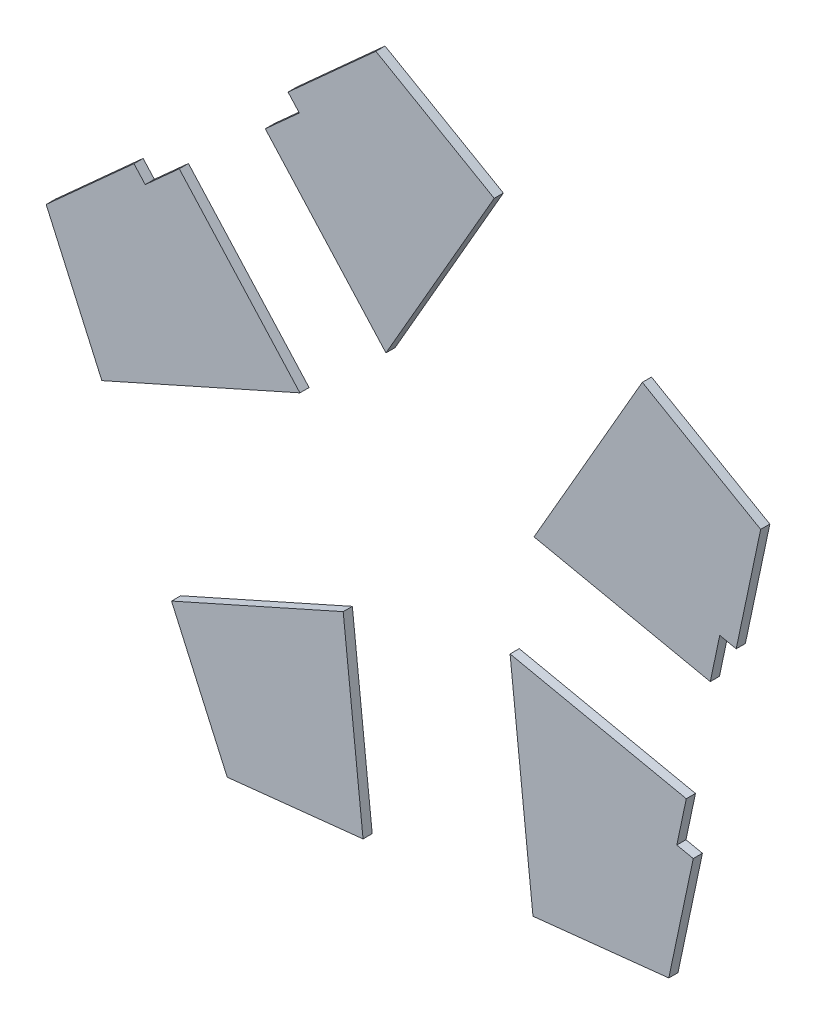
SolidWorks part; units mm, degrees
ref_plane "Front Plane" through (0, 0, 0) normal (0, 0, 1) x (1, 0, 0)
ref_plane "Top Plane" through (0, 0, 0) normal (0, 1, 0) x (1, 0, 0)
ref_plane "Right Plane" through (0, 0, 0) normal (1, 0, 0) x (0, 0, -1)
sketch "Sketch15" plane through (0, 0, 0) normal (0, 0, 1) x (1, 0, 0)
  line L0 (37.7834, -91.019) -> (30.8688, -25.9063)
  line L2 (30.8688, -25.9063) -> (88.5339, -38.0985)
  line L3 (88.5339, -38.0985) -> (85.4311, -52.774)
  line L4 (85.4311, -52.774) -> (90.8121, -53.9117)
  line L5 (90.8121, -53.9117) -> (82.808, -91.7686)
  line L6 (82.808, -91.7686) -> (38.3642, -96.4882)
  line L7 (38.3642, -96.4882) -> (37.7834, -91.019)
  line L8 (74.1362, 72.7022) -> (38.7131, 11.1945)
  line L10 (38.7131, 11.1945) -> (96.3782, -0.9976)
  line L11 (96.3782, -0.9976) -> (99.4811, 13.6779)
  line L12 (99.4811, 13.6779) -> (104.8621, 12.5402)
  line L13 (104.8621, 12.5402) -> (112.8662, 50.3971)
  line L14 (112.8662, 50.3971) -> (74.1362, 72.7022)
  line L15 (25.6771, 100.6105) -> (-9.7461, 39.1028)
  line L17 (-9.7461, 39.1028) -> (-49.2317, 82.8612)
  line L18 (-49.2317, 82.8612) -> (-38.0954, 92.9102)
  line L19 (-38.0954, 92.9102) -> (-41.78, 96.9935)
  line L20 (-41.78, 96.9935) -> (-13.0529, 122.9157)
  line L21 (-13.0529, 122.9157) -> (25.6771, 100.6105)
  line L22 (-102.7107, -15.2411) -> (-37.8995, 13.6984)
  line L25 (-37.8995, 13.6984) -> (-77.3852, 57.4568)
  line L26 (-77.3852, 57.4568) -> (-88.5215, 47.4078)
  line L27 (-88.5215, 47.4078) -> (-92.2062, 51.4912)
  line L28 (-92.2062, 51.4912) -> (-120.9333, 25.569)
  line L29 (-120.9333, 25.569) -> (-102.7107, -15.2411)
  line L30 (-79.9106, -66.303) -> (-23.7402, -41.2218)
  line L33 (-79.9106, -66.303) -> (-61.688, -107.1132)
  line L34 (-61.688, -107.1132) -> (-17.2442, -102.3935)
  line L39 (-17.2442, -102.3935) -> (-23.7402, -41.2218)
extrude "Boss-Extrude1" add sketch "Sketch15" along normal blind 3 contours L34 L39 L30 L33 | L28 L29 L22 L25 L26 L27 | L21 L20 L19 L18 L17 L15 | L13 L14 L8 L10 L11 L12 | L2 L3 L4 L5 L6 L7 L0
